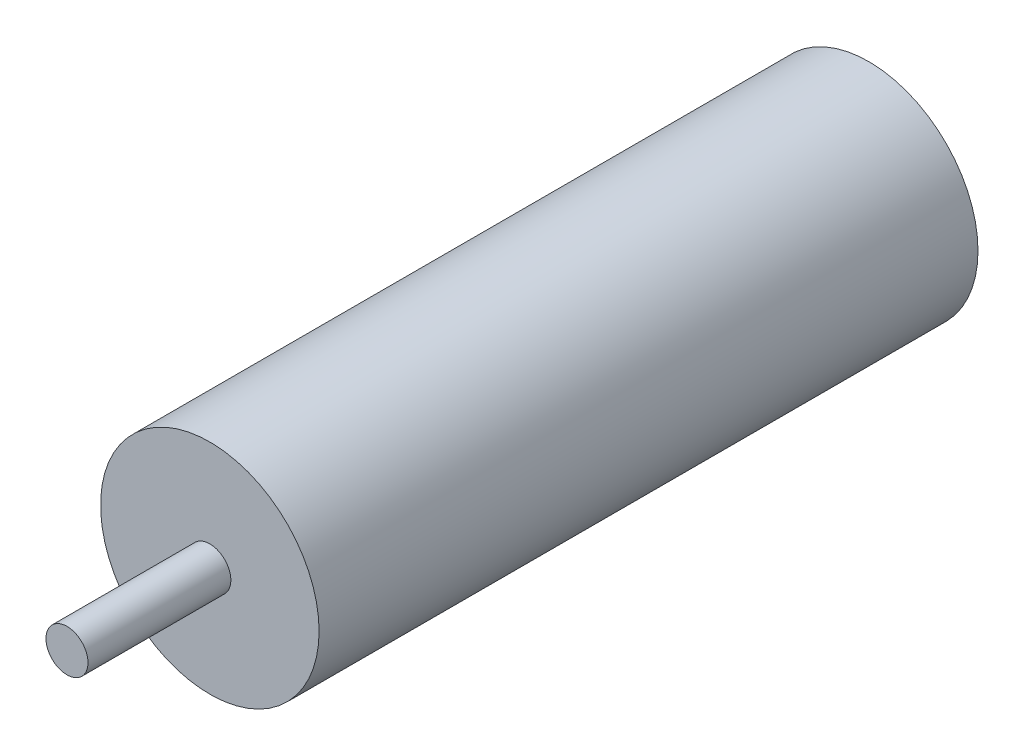
SolidWorks part; units mm, degrees
ref_plane "Plan de face" through (0, 0, 0) normal (0, 0, 1) x (1, 0, 0)
ref_plane "Plan de dessus" through (0, 0, 0) normal (0, 1, 0) x (1, 0, 0)
ref_plane "Plan de droite" through (0, 0, 0) normal (1, 0, 0) x (0, 0, -1)
sketch "Esquisse1" plane through (0, 0, 0) normal (0, 0, 1) x (1, 0, 0)
  circle A0 centre (0, 0) radius 13
  dimension "D1" = 26
extrude "Boss.-Extru.1" add sketch "Esquisse1" along normal blind 78.4
sketch "Esquisse2" plane through (0, 0, 78.4) normal (0, 0, 1) x (1, 0, 0)
  circle A0 centre (0, 0) radius 2.5
  dimension "D1" = 5
extrude "Boss.-Extru.2" add sketch "Esquisse2" along normal blind 17
